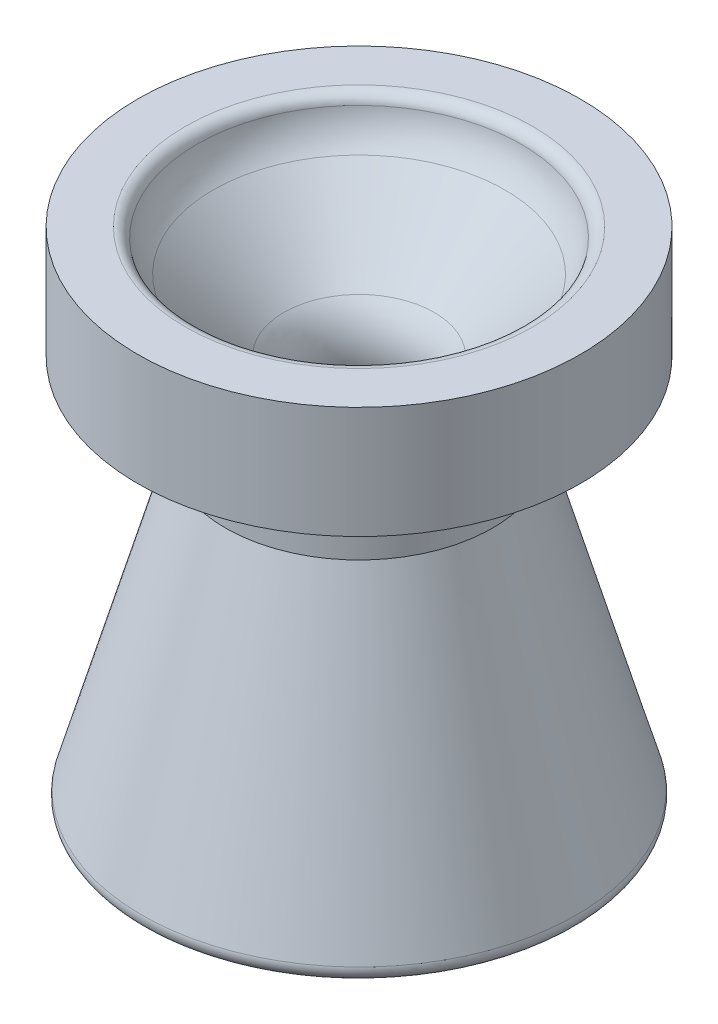
SolidWorks part; units mm, degrees
ref_plane "Front Plane" through (0, 0, 0) normal (0, 0, 1) x (1, 0, 0)
ref_plane "Top Plane" through (0, 0, 0) normal (0, 1, 0) x (1, 0, 0)
ref_plane "Right Plane" through (0, 0, 0) normal (1, 0, 0) x (0, 0, -1)
sketch "Sketch2" plane through (0, 0, 0) normal (0, 0, 1) x (1, 0, 0)
  line L0 (0, 0) -> (6.35, 0) construction
  line L1 (6.35, 0) -> (12.7, 0) construction
  line L2 (-5.08, 0) -> (-5.08, 16.6905) construction
  line L3 (-5.08, -38.1) -> (-5.08, 0) construction
  line L4 (0, 0) -> (-5.08, 0) construction
  line L6 (4.4901, 4.4901) -> (-3.2201, 12.2004)
  line L7 (-5.08, -38.1) -> (-5.08, 16.6905) construction
  line L8 (12.7, 19.6494) -> (12.7, -22.8567) construction
  line L9 (-5.08, -38.1) -> (-11.43, -38.1)
  line L10 (-11.43, -38.1) -> (-1.8599, -4.4901)
  line L11 (-1.8599, 4.4901) -> (-1.8599, -4.4901)
  line L12 (-1.8599, 4.4901) -> (-11.43, 4.4901)
  line L13 (-11.43, 16.6905) -> (-5.08, 16.6905)
  line L14 (4.4901, 4.4901) -> (-1.8599, 4.4901) construction
  line L15 (4.4901, -4.4901) -> (-1.8599, -4.4901) construction
  line L16 (-11.43, 4.4901) -> (-11.43, 16.6905)
  arc A0 (4.4901, 4.4901) -> (4.4901, -4.4901) centre (0, 0) cw
  arc A1 (-3.2201, 12.2004) -> (-5.08, 16.6905) centre (1.27, 16.6905) cw
  parabola Q0 (-5.08, -38.1) -> (4.4901, -4.4901) focus (13.2969, -10.3149) apex (7.7045, -1.8593)
  point P4 (6.35, 0)
  dimension "D1" = 6.35
  dimension "D6" = 6.35
  dimension "D2" = 90
  dimension "D3" = 6.35
  dimension "D4" = 5.08
  dimension "D5" = 38.1
  dimension "D7" = 6.35
  dimension "D8" = 6.35
  dimension "D9" = 6.35
revolve "Revolve1" add sketch "Sketch2" angle 360 about L8
fillet "Fillet1" radius 1.27 2 edges at (-11.43, -38.1, 0) (-5.08, 16.6905, 0)
